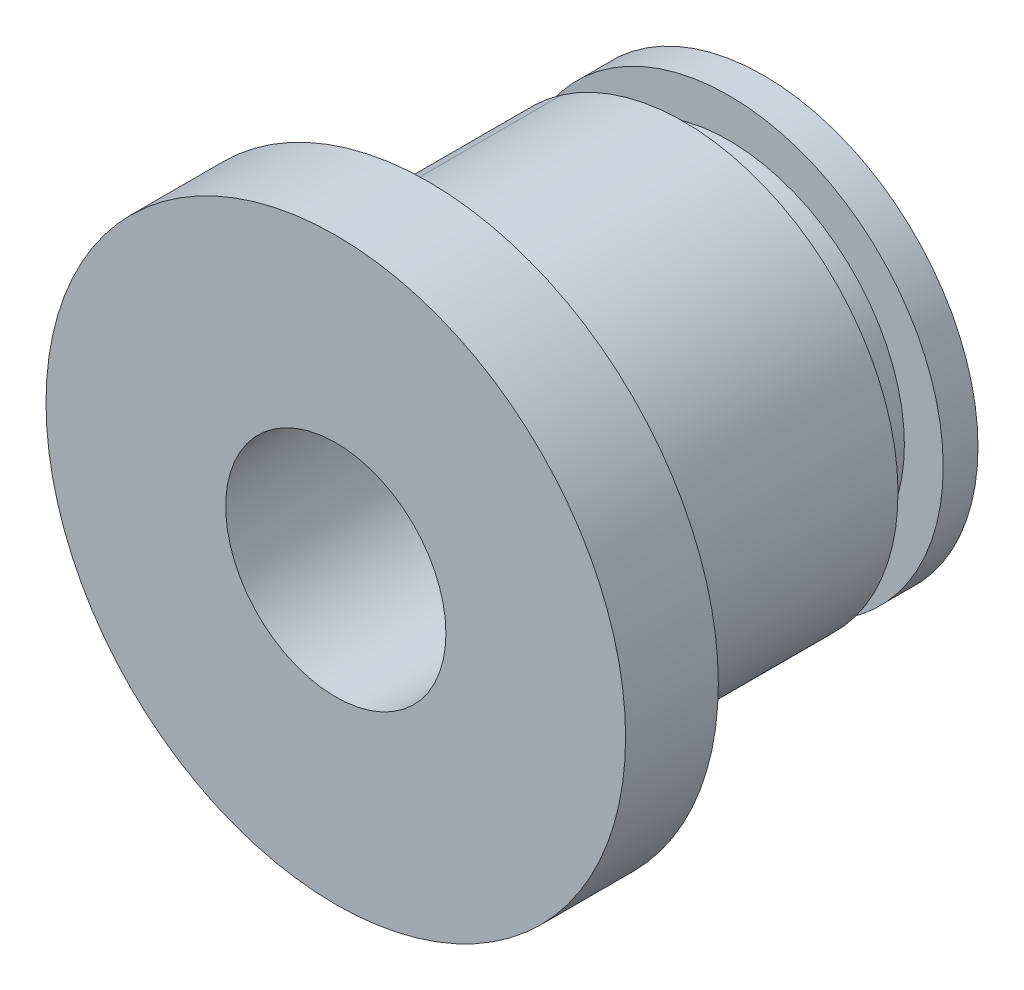
SolidWorks part; units mm, degrees
material "AISI 4130 Steel, annealed at 865C"
ref_plane "Front Plane" through (0, 0, 0) normal (0, 0, 1) x (1, 0, 0)
ref_plane "Top Plane" through (0, 0, 0) normal (0, 1, 0) x (1, 0, 0)
ref_plane "Right Plane" through (0, 0, 0) normal (1, 0, 0) x (0, 0, -1)
sketch "Sketch1" plane through (0, 0, 0) normal (0, 0, 1) x (1, 0, 0)
  circle A0 centre (0, 0) radius 6.35
  dimension "D1" = 12.7
extrude "Boss-Extrude1" add sketch "Sketch1" along normal blind 2.032
sketch "Sketch2" plane through (0, 0, 0) normal (0, 0, -1) x (-1, 0, 0)
  circle A0 centre (0, 0) radius 4.699
  dimension "D1" = 9.398
extrude "Boss-Extrude2" add sketch "Sketch2" along normal blind 7.3406
ref_axis "Axis1" through (0, 0, 6.5491) along (0, 0, -1)
sketch "Sketch4" plane through (0, 0, 0) normal (1, 0, 0) x (0, 0, -1)
  line L0 (0, -4.699) -> (0, 4.699) construction
  line L1 (0, -4.699) -> (0, 4.699)
  line L2 (5.588, 4.699) -> (5.588, -4.699)
  line L3 (7.3406, 4.699) -> (0, 4.699) construction
  line L4 (0, -4.699) -> (7.3406, -4.699) construction
  line L5 (0, 4.699) -> (7.3406, 4.699)
  line L6 (0, -4.699) -> (7.3406, -4.699)
  line L7 (7.3406, -4.699) -> (7.3406, 4.699) construction
  line L8 (6.5786, 4.699) -> (6.5786, -4.699)
  line L9 (5.588, 3.8481) -> (6.5786, 3.8481)
  line L10 (5.588, 0) -> (6.5786, 0)
  dimension "D1" = 5.588
  dimension "D2" = 0.9906
  dimension "D3" = 3.8481
revolve "Cut-Revolve1" cut sketch "Sketch4" angle 360 about axis through (0, 0, 6.5491) along (0, 0, -1)
sketch3d "3DSketch1"
  line L0 (2.6418, -3.886, 0) -> (-2.6678, 3.8683, 0)
  circle A2 centre (0, 0, 0) radius 4.699 construction
  point P4 (0, 0, -4.699)
split line "Split Line3"
sketch "Sketch8" plane through (0, 0, 2.032) normal (0, 0, 1) x (1, 0, 0)
  circle A0 centre (0, 0) radius 2.413
extrude "Cut-Extrude2" cut sketch "Sketch8" against normal blind 15.24
